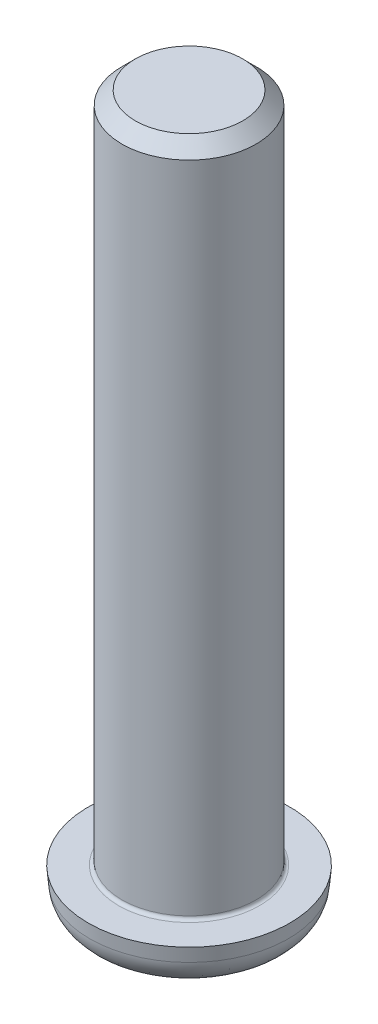
SolidWorks part; units mm, degrees
ref_plane "Front" through (0, 0, 0) normal (0, 0, 1) x (1, 0, 0)
ref_plane "Top" through (0, 0, 0) normal (0, 1, 0) x (1, 0, 0)
ref_plane "Right" through (0, 0, 0) normal (1, 0, 0) x (0, 0, -1)
sketch "Sketch1" plane through (0, 0, 0) normal (1, 0, 0) x (0, 0, -1)
  line L0 (0, 0) -> (0, 1.235) construction
  line L1 (-1, 0) -> (-1, 10)
  line L2 (-1, 10) -> (0, 10)
  line L3 (0, 10) -> (0, -0.6)
  line L4 (0, -0.6) -> (-1.2, -0.6)
  line L5 (-1, 0) -> (-1.5, 0)
  line L6 (-1.5, 0) -> (-1.4816, -0.21)
  line L7 (0, 0) -> (-1, 0) construction
  line L8 (-1.5, 0) -> (-1.5, -1.0829) construction
  arc A0 (-1.4816, -0.21) -> (-1.2, -0.6) centre (-1.0141, -0.1691) ccw
  dimension "d" = 2
  dimension "H" = 0.6
  dimension "D1" = 2.4
  dimension "DD" = 3
  dimension "D2" = 5
  dimension "D3" = 0.39
  dimension "L" = 10
revolve "Revolve1" add sketch "Sketch1" angle 360 about L3
fillet "Fillet5" radius 0.2 1 edges at (0, -0.6, 1.2)
sketch "Sketch2" plane through (0, -0.6, 0) normal (0, -1, 0) x (1, 0, 0)
  line L0 (-2.0062, 0) -> (2.7281, 0) construction
  line L1 (0, 2.3126) -> (0, -2.1951) construction
  line L2 (0.1573, 0.1573) -> (0.925, 0.1573)
  line L3 (-0.1573, 0.925) -> (0.1572, 0.925)
  line L4 (-0.1573, 0.925) -> (-0.1573, 0.1572)
  line L5 (-0.1573, -0.925) -> (0.1573, -0.925)
  line L6 (0.1572, 0.925) -> (0.1573, 0.1573)
  line L7 (-0.925, 0.1572) -> (-0.1573, 0.1572)
  line L8 (-0.925, 0.1572) -> (-0.925, -0.1573)
  line L9 (-0.925, -0.1573) -> (-0.1573, -0.1573)
  line L10 (0.925, 0.1573) -> (0.925, -0.1573)
  line L11 (-0.1573, -0.1573) -> (-0.1573, -0.925)
  line L12 (0.1573, -0.1573) -> (0.925, -0.1573)
  line L13 (0.1573, -0.1573) -> (0.1573, -0.925)
  line L14 (-0.1573, -0.925) -> (-0.1573, -1.325) construction
  dimension "M" = 1.85
  dimension "D2" = 1.85
  dimension "D3" = 0.3145
  dimension "p" = 0.4
extrude "Cut-Extrude1" cut sketch "Sketch2" against normal blind 1.27 draft 3
fillet "Fillet4" radius 0.05 1 edges at (0, 0, 1)
chamfer "Chamfer1" distance 0.2 angle 45 1 edges at (0, 10, 1)
other "Freeze***"
equation "\"D2@Sketch2\" = \"M@Sketch2\""
equation "\"D3@Sketch2\" = \"M@Sketch2\" * 0.17"
equation "\"D1@Sketch1\" = \"DD@Sketch1\" * 0.8"
equation "\"D3@Sketch1\" = \"H@Sketch1\" * 0.65"
equation "\"D1@Chamfer1\" = \"p@Sketch2\" / 2"
